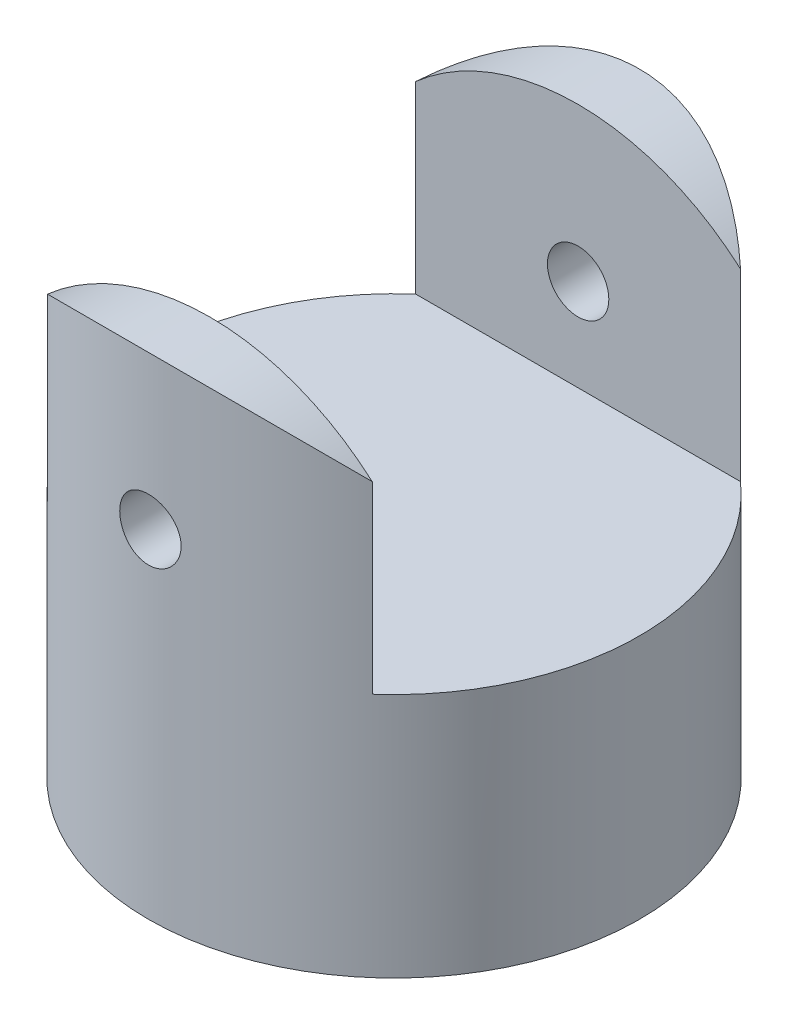
SolidWorks part; units mm, degrees
ref_plane "Front Plane" through (0, 0, 0) normal (0, 0, 1) x (1, 0, 0)
ref_plane "Top Plane" through (0, 0, 0) normal (0, 1, 0) x (1, 0, 0)
ref_plane "Right Plane" through (0, 0, 0) normal (1, 0, 0) x (0, 0, -1)
sketch "Sketch1" plane through (0, 0, 0) normal (0, 1, 0) x (1, 0, 0)
  circle A0 centre (0, 0) radius 50.8
  dimension "D1" = 101.6
extrude "Boss-Extrude1" add sketch "Sketch1" along normal blind 101.6
sketch "Sketch2" plane through (0, 0, 0) normal (0, 0, 1) x (1, 0, 0)
  line L0 (-50.8, 101.6) -> (-50.8, 0) construction
  line L1 (50.8, 0) -> (50.8, 101.6) construction
  line L2 (50.8, 101.6) -> (-50.8, 101.6) construction
  line L3 (-50.8, 50.8) -> (-71.7433, 50.8)
  line L4 (-71.7433, 50.8) -> (-71.7433, 136.3178)
  line L5 (-71.7433, 136.3178) -> (67.4245, 136.3178)
  line L6 (67.4245, 136.3178) -> (67.4245, 50.8)
  line L7 (67.4245, 50.8) -> (50.8, 50.8)
  arc A0 (-50.8, 50.8) -> (50.8, 50.8) centre (0, 50.8) cw
  circle A1 centre (0, 69.85) radius 6.35
  point P14 (0, 0)
  dimension "D1" = 19.05
  dimension "D2" = 12.7
extrude "Cut-Extrude1" cut sketch "Sketch2" against normal blind 101.6 and the other way blind 96.52
sketch "Sketch3" plane through (0, 0, 0) normal (1, 0, 0) x (0, 0, -1)
  line L0 (0, 143.5049) -> (0, -44.6309) construction
  line L1 (-38.1, 133.2765) -> (38.1, 133.2765)
  line L2 (-38.1, 133.2765) -> (-38.1, 50.8)
  line L3 (-38.1, 50.8) -> (38.1, 50.8)
  line L4 (38.1, 133.2765) -> (38.1, 50.8)
  point P4 (0, 50.8)
  dimension "D1" = 76.2
extrude "Cut-Extrude2" cut sketch "Sketch3" against normal blind 86.36 and the other way blind 103.886
ref_plane "Plane1" through (0, 0, 0) normal (0, 0, 1) x (1, 0, 0)
ref_plane "Plane2" through (0, 69.85, 0) normal (0, -1, 0) x (-1, 0, 0)
